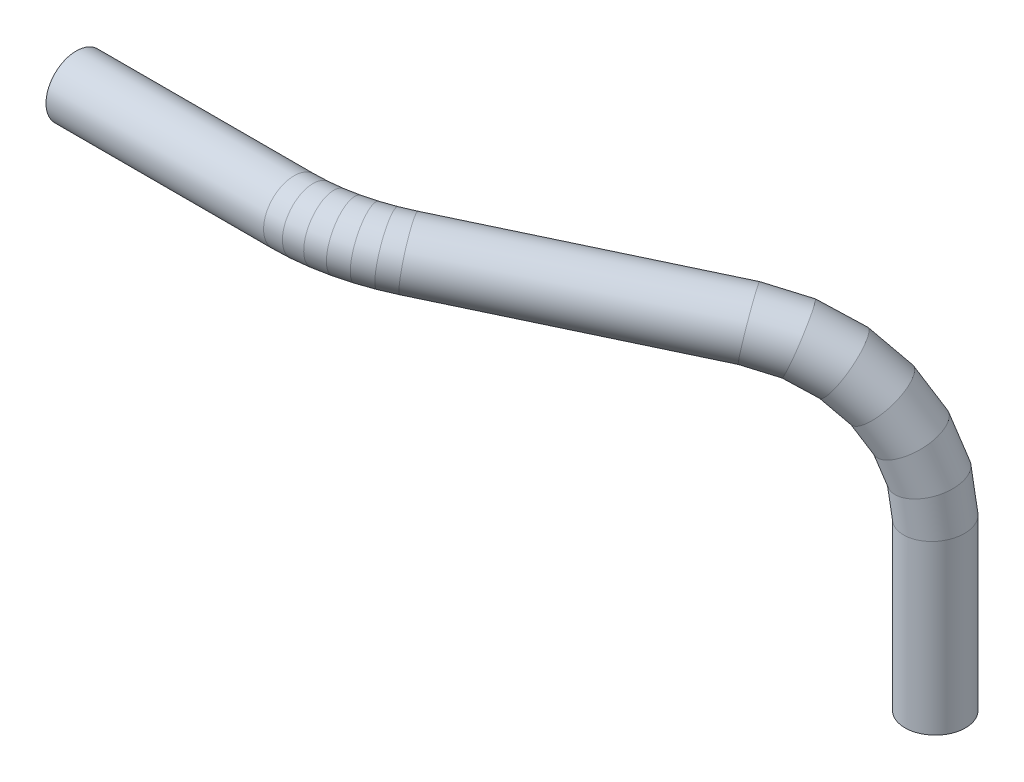
SolidWorks part; units mm, degrees
ref_plane "Front Plane" through (0, 0, 0) normal (0, 0, 1) x (1, 0, 0)
ref_plane "Top Plane" through (0, 0, 0) normal (0, 1, 0) x (1, 0, 0)
ref_plane "Right Plane" through (0, 0, 0) normal (1, 0, 0) x (0, 0, -1)
sketch3d "Path"
  line L0 (28.2, 105.2456, 38.3063) -> (62.3415, 105.2456, 38.3063)
  line L1 (62.3415, 105.2456, 38.3063) -> (64.8082, 105.2188, 38.182)
  line L2 (64.8082, 105.2188, 38.182) -> (67.2489, 105.1389, 37.8105)
  line L3 (67.2489, 105.1389, 37.8105) -> (69.6375, 105.0065, 37.1958)
  line L4 (69.6375, 105.0065, 37.1958) -> (71.9489, 104.8233, 36.3443)
  line L5 (71.9489, 104.8233, 36.3443) -> (74.1585, 104.5909, 35.2651)
  line L6 (74.1585, 104.5909, 35.2651) -> (76.243, 104.3121, 33.9695)
  line L7 (76.243, 104.3121, 33.9695) -> (107.8357, 99.5881, 12.0234)
  line L8 (107.8357, 99.5881, 12.0234) -> (112.4437, 98.1977, 8.8224)
  line L9 (112.4437, 98.1977, 8.8224) -> (116.645, 95.5062, 5.904)
  line L10 (116.645, 95.5062, 5.904) -> (120.1959, 91.6697, 3.4373)
  line L11 (120.1959, 91.6697, 3.4373) -> (122.8905, 86.9107, 1.5655)
  line L12 (122.8905, 86.9107, 1.5655) -> (124.5724, 81.5053, 0.3971)
  line L13 (124.5724, 81.5053, 0.3971) -> (125.1441, 75.767, 0)
  line L14 (125.1441, 75.767, 0) -> (125.1441, 49.4, 0)
ref_plane "Start Plane" through (28.2, 0, 0) normal (1, 0, 0) x (0, 0, -1)
sketch "Profile" plane through (28.2, 0, 0) normal (1, 0, 0) x (0, 0, -1)
  circle A0 centre (-38.3063, 105.2456) radius 4.7625
  circle A1 centre (-38.3063, 105.2456) radius 3.8735
sweep "Tube" add profiles "Profile" path "Path"
